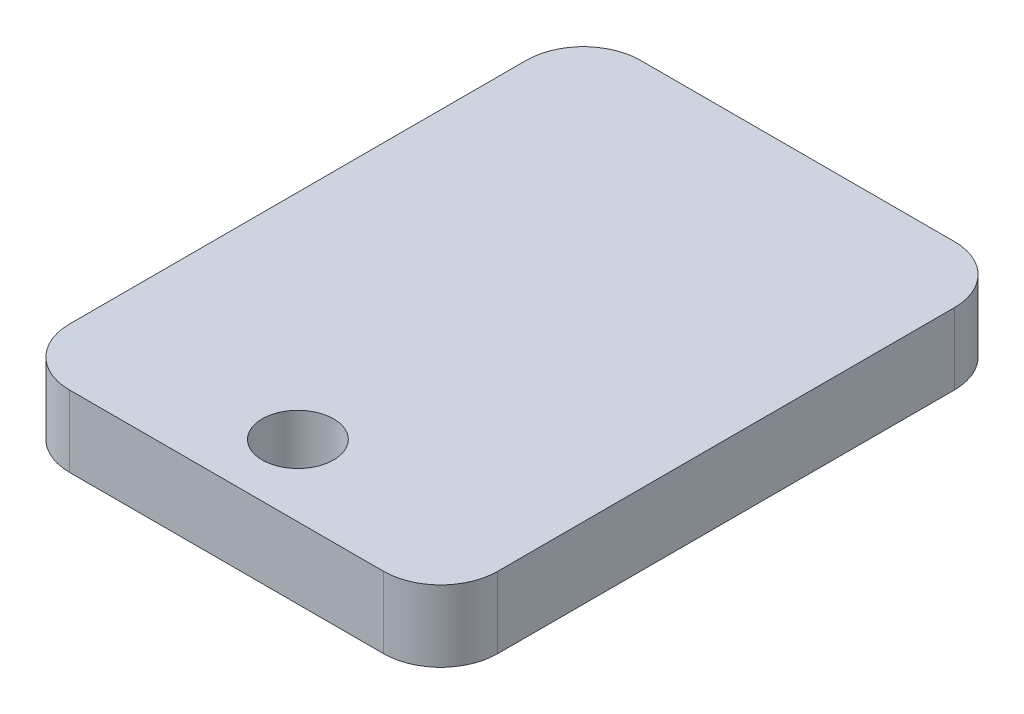
SolidWorks part; units mm, degrees
ref_plane "Front Plane" through (0, 0, 0) normal (0, 0, 1) x (1, 0, 0)
ref_plane "Top Plane" through (0, 0, 0) normal (0, 1, 0) x (1, 0, 0)
ref_plane "Right Plane" through (0, 0, 0) normal (1, 0, 0) x (0, 0, -1)
sketch "Sketch2" plane through (0, 0, 0) normal (0, 1, 0) x (1, 0, 0)
  line L0 (0, -25.4) -> (0, -19.05) construction
  line L1 (-13.97, -25.4) -> (13.97, -25.4)
  line L2 (-19.05, -20.32) -> (-19.05, 20.32)
  line L3 (-13.97, 25.4) -> (13.97, 25.4)
  line L4 (19.05, -20.32) -> (19.05, 20.32)
  line L5 (-19.05, -25.4) -> (19.05, 25.4) construction
  line L6 (-19.05, 25.4) -> (19.05, -25.4) construction
  arc A0 (13.97, -25.4) -> (19.05, -20.32) centre (13.97, -20.32) ccw
  arc A1 (-13.97, -25.4) -> (-19.05, -20.32) centre (-13.97, -20.32) cw
  arc A2 (13.97, 25.4) -> (19.05, 20.32) centre (13.97, 20.32) cw
  arc A3 (-19.05, 20.32) -> (-13.97, 25.4) centre (-13.97, 20.32) cw
  circle A4 centre (0, -19.05) radius 3.175
  point P0 (0, 0)
  dimension "D1" = 50.8
  dimension "D3" = 5.08
  dimension "D5" = 6.35
  dimension "D2" = 38.1
  dimension "D4" = 6.35
extrude "Boss-Extrude1" add sketch "Sketch2" along normal mid plane 6.35
equation "\"airframeInnerDiameter\"= 6in"
equation "\"outerDiameter\"= 6.112in"
equation "\"airframeBulkheadThickness\"= 0.125in"
equation "\"payloadAirframeLength\"= 10in"
equation "\"payloadInnerDiameter\"= 6in - 0.056in"
equation "\"payloadOuterDiameter\"= \"airframeInnerDiameter\""
equation "\"payloadLength\"= 11in"
equation "\"payloadBand\"= 2in"
equation "\"payloadOffsetFromAft\"= 6in"
equation "\"upperAirframeLength\"= 25in"
equation "\"recoveryBayInnerDiameter\"= 5.888in"
equation "\"recoveryLength\"= 8in"
equation "\"recoveryBand\"= 2in"
equation "\"recoveryCouplerOuter\"=\"airframeInnerDiameter\""
equation "\"recoveryOffsetFromAft\"= 3in"
equation "\"midAirframeLength\"= 20in"
equation "\"atsLength\"= 11in"
equation "\"atsInner\"= 5.888in"
equation "\"atsBand\"= 2in"
equation "\"atsCouplerOuter\"=\"airframeInnerDiameter\""
equation "\"atsOffsetFromAft\"= 3in"
equation "\"lowerAirframeLength\"= 40in"
equation "\"motorTubeOuterDiameter\"= 4.25in"
equation "\"motorTubeInnerDiameter\"= 4in"
equation "\"motorTubeLength\"= 32in"
equation "\"centeringRingOuterDiameter\"= \"airframeInnerDiameter\""
equation "\"centeringRingInnerDiameter\"= \"motorTubeOuterDiameter\""
equation "\"centeringRingThickness\"= 0.375in"
equation "\"topCenteringRingOffsetFromAft\"= 16.7in"
equation "\"bottomCenteringRingOffsetFromAft\"= 0.3in"
equation "\"finSlotLength\"= 8in"
equation "\"finSlotOffsetFromAft\"= 3in"
equation "\"finSlotWidth\"= 0.187in"
equation "\"motorCasingOuterDiameter\"= 3in"
equation "\"motorCasingCenteringRingThickness\"= 0.25in"
